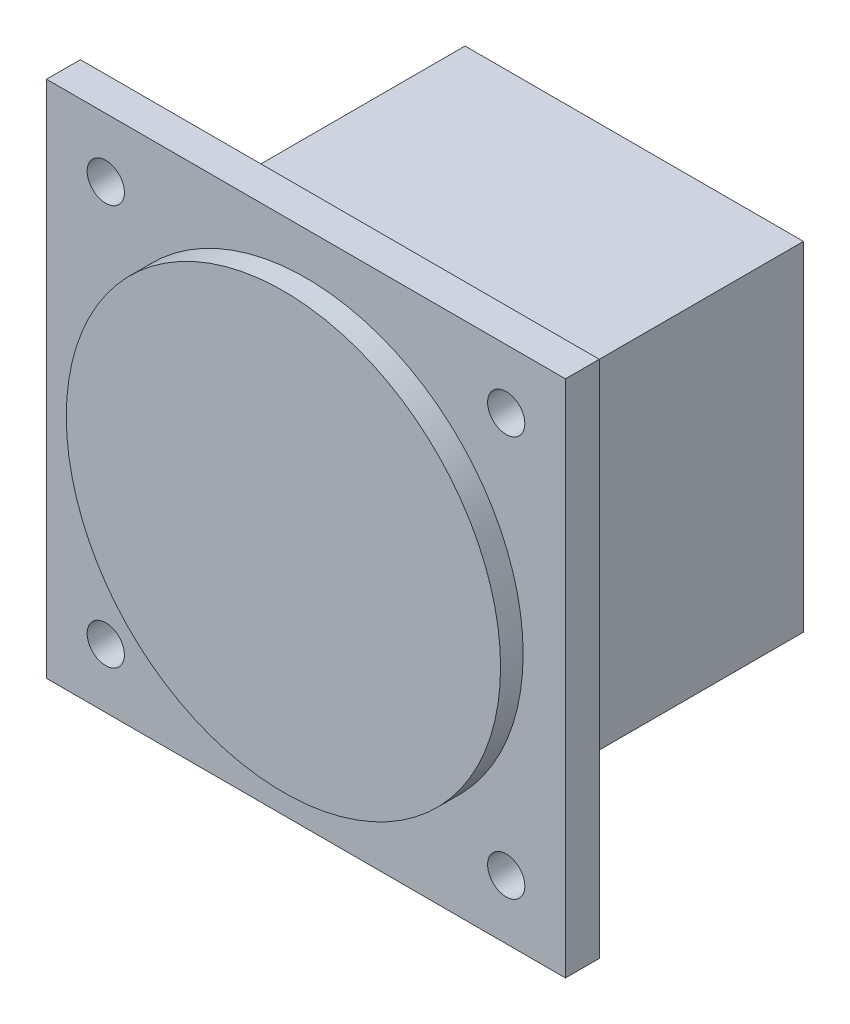
SolidWorks part; units mm, degrees
ref_plane "Front Plane" through (0, 0, 0) normal (0, 0, 1) x (1, 0, 0)
ref_plane "Top Plane" through (0, 0, 0) normal (0, 1, 0) x (1, 0, 0)
ref_plane "Right Plane" through (0, 0, 0) normal (1, 0, 0) x (0, 0, -1)
sketch "Sketch1" plane through (0, 0, 0) normal (0, 0, 1) x (1, 0, 0)
  line L5 (-23, 23) -> (23, 23)
  line L6 (-23, 23) -> (-23, -23)
  line L7 (-23, -23) -> (23, -23)
  line L8 (23, 23) -> (23, -23)
  line L9 (-23, 23) -> (23, -23) construction
  line L10 (-23, -23) -> (23, 23) construction
  circle A2 centre (0, 0) radius 20
  arc A3 (-23, -10.0504) -> (-10.0504, -23) centre (0, 0) ccw
  arc A4 (-10.0504, 23) -> (-23, 10.0504) centre (0, 0) ccw
  arc A7 (23, 10.0504) -> (10.0504, 23) centre (0, 0) ccw
  arc A8 (10.0504, -23) -> (23, -10.0504) centre (0, 0) ccw
  circle A9 centre (-17.7484, -17.7484) radius 1.65
  circle A10 centre (-17.7484, 17.7484) radius 1.65
  circle A11 centre (17.7484, 17.7484) radius 1.65
  circle A12 centre (17.7484, -17.7484) radius 1.65
  point P26 (0, 0)
  dimension "D1" = 40
  dimension "D4" = 46
  dimension "D2" = 50.2
  dimension "D5" = 3.3
  dimension "D3" = 46
  dimension "D6" = 4
extrude "Boss-Extrude1" add sketch "Sketch1" along normal blind 3 contours A12 A8 L8 A7 A11 L5 A4 A10 L6 A3 A9 L7 A2 | A2 | A11 A7 L8 L5 | A10 A4 L5 L6 | A12 A8 L7 L8 | A9 A3 L6 L7
sketch "Sketch2" plane through (0, 0, 3) normal (0, 0, 1) x (1, 0, 0)
  line L0 (0, 23) -> (0, -23) construction
  line L1 (-23, 23) -> (23, 23) construction
  line L2 (-23, -23) -> (23, -23) construction
  line L3 (-23, 0) -> (23, 0) construction
  line L4 (-23, 23) -> (-23, -23) construction
  line L5 (23, 23) -> (23, -23) construction
  circle A0 centre (0, 0) radius 19.25
  dimension "D1" = 38.5
extrude "Boss-Extrude2" add sketch "Sketch2" along normal blind 2
sketch "Sketch3" plane through (0, 0, 0) normal (0, 0, -1) x (-1, 0, 0)
  line L1 (-15, 15) -> (15, 15)
  line L2 (-15, 15) -> (-15, -15)
  line L3 (-15, -15) -> (15, -15)
  line L4 (15, 15) -> (15, -15)
  line L5 (-15, 15) -> (15, -15) construction
  line L6 (-15, -15) -> (15, 15) construction
  point P0 (0, 0)
  dimension "D1" = 30
  dimension "D2" = 30
extrude "Boss-Extrude3" add sketch "Sketch3" along normal blind 26.1
